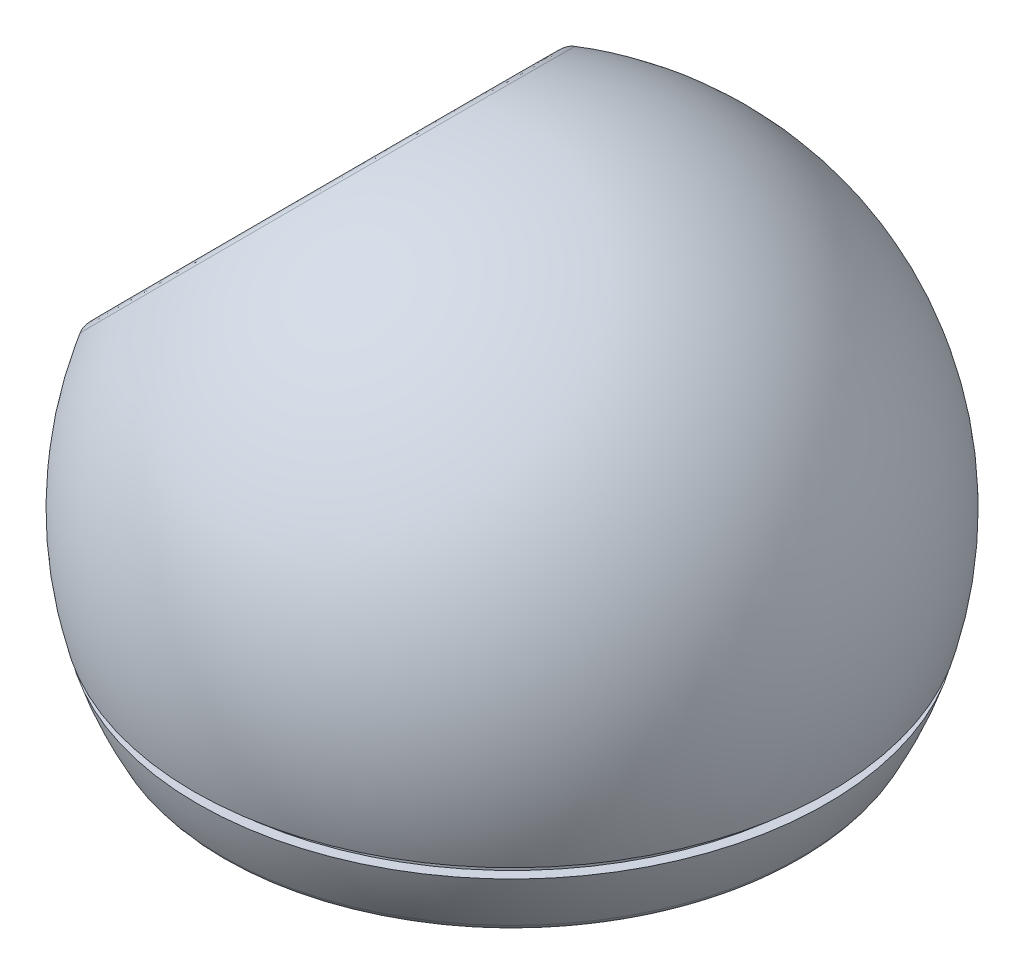
SolidWorks part; units mm, degrees
ref_plane "Front Plane" through (0, 0, 0) normal (0, 0, 1) x (1, 0, 0)
ref_plane "Top Plane" through (0, 0, 0) normal (0, 1, 0) x (1, 0, 0)
ref_plane "Right Plane" through (0, 0, 0) normal (1, 0, 0) x (0, 0, -1)
sketch "Sketch2" plane through (0, 0, 0) normal (1, 0, 0) x (0, 0, -1)
  line L0 (0, 0) -> (0, 55.0684) construction
  line L1 (0, 40) -> (0, -40)
  arc A0 (0, 40) -> (0, -40) centre (0, 0) ccw
  dimension "D1" = 80
revolve "Revolve4" add sketch "Sketch2" angle 360 about L0
sketch "Sketch3" plane through (0, 0, 0) normal (0, 0, 1) x (1, 0, 0)
  line L0 (0, 0) -> (0, -20) construction
  line L2 (-40, -20) -> (40, -20)
  line L3 (-40, -20) -> (-40, -70)
  line L4 (-40, -70) -> (40, -70)
  line L5 (40, -20) -> (40, -70)
  point P7 (0, -20)
  dimension "D1" = 20
  dimension "D2" = 80
  dimension "D3" = 50
extrude "Cut-Extrude1" cut sketch "Sketch3" against normal through all and the other way through all
sketch "Sketch4" plane through (0, 0, 0) normal (0, 0, 1) x (1, 0, 0)
  line L0 (-22.3051, 0) -> (0, 0) construction
  line L1 (0, 0) -> (-22.6274, 22.6274) construction
  line L2 (-40.2644, 4.9092) -> (-4.9904, 40.3457)
  line L3 (-4.9904, 40.3457) -> (-21.3315, 54.0701)
  line L4 (-21.3315, 54.0701) -> (-80.217, 4.9092)
  line L5 (-80.217, 4.9092) -> (-40.2644, 4.9092)
  point P6 (-22.6274, 22.6274)
  dimension "D1" = 45
  dimension "D2" = 50
  dimension "D3" = 32
extrude "Cut-Extrude2" cut sketch "Sketch4" against normal through all and the other way through all
sketch "Sketch5" plane through (-22.6793, 22.5753, 0) normal (-0.7087, 0.7055, 0) x (0, 0, 1)
  line L0 (-15.8, 18.6) -> (15.8, 18.6) construction
  line L1 (-15.8, 18.6) -> (-15.8, -21) construction
  line L2 (-15.8, -21) -> (15.8, -21) construction
  line L3 (15.8, 18.6) -> (15.8, -21) construction
  line L4 (-15.8, 16.2) -> (15.8, 16.2) construction
  line L5 (-14.2, 18.6) -> (-14.2, -21) construction
  line L6 (14.2, 18.6) -> (14.2, -21) construction
  line L7 (-15.8, -16.2) -> (15.8, -16.2) construction
  line L8 (-20.2, 22.2) -> (20.2, 22.2) construction
  line L9 (-9.2, 16.2) -> (9.2, 16.2)
  line L10 (-14.2, 11.2) -> (-14.2, -11.2)
  line L11 (-9.2, -16.2) -> (9.2, -16.2)
  line L12 (14.2, 11.2) -> (14.2, -11.2)
  line L13 (20.2, 22.2) -> (20.2, -22.2) construction
  line L14 (-20.2, -22.2) -> (20.2, -22.2) construction
  line L15 (-20.2, 22.2) -> (-20.2, -22.2) construction
  line L16 (0, 16.2) -> (0, -16.2) construction
  line L17 (15.2, 11.2) -> (15.2, -11.2)
  line L18 (-9.2, -17.2) -> (9.2, -17.2)
  line L19 (-15.2, 11.2) -> (-15.2, -11.2)
  line L20 (-9.2, 17.2) -> (9.2, 17.2)
  arc A0 (9.2, -16.2) -> (14.2, -11.2) centre (9.2, -11.2) ccw
  arc A1 (-14.2, -11.2) -> (-9.2, -16.2) centre (-9.2, -11.2) ccw
  arc A2 (9.2, 16.2) -> (14.2, 11.2) centre (9.2, 11.2) cw
  arc A3 (-9.2, 16.2) -> (-14.2, 11.2) centre (-9.2, 11.2) ccw
  arc A4 (9.2, 17.2) -> (15.2, 11.2) centre (9.2, 11.2) cw
  arc A5 (9.2, -17.2) -> (15.2, -11.2) centre (9.2, -11.2) ccw
  arc A6 (-15.2, -11.2) -> (-9.2, -17.2) centre (-9.2, -11.2) ccw
  arc A7 (-9.2, 17.2) -> (-15.2, 11.2) centre (-9.2, 11.2) ccw
  point P24 (14.2, -16.2)
  point P31 (-14.2, 16.2)
  dimension "D1" = 5
  dimension "D2" = 1
extrude "Cut-Extrude3" cut sketch "Sketch5" against normal blind 1
sketch "Sketch6" plane through (-22.6793, 22.5753, 0) normal (-0.7087, 0.7055, 0) x (0, 0, 1)
  line L0 (0, 0) -> (0, -20) construction
  circle A0 centre (0, -20) radius 1
  circle A1 centre (3, -20) radius 1
  circle A2 centre (6, -20) radius 1
  circle A3 centre (-3, -20) radius 1
  circle A4 centre (-6, -20) radius 1
  dimension "D2" = 3
  dimension "D1" = 20
  dimension "D3" = 3
extrude "Cut-Extrude4" cut sketch "Sketch6" against normal blind 1
fillet "Fillet1" radius 2 1 edges at (-5.7477, 39.5849, 0)
sketch "Sketch7" plane through (0, 0, 0) normal (1, 0, 0) x (0, 0, -1)
  line L0 (-34.641, -20) -> (34.641, -20) construction
  line L1 (-39.8854, -10.5) -> (-36.8854, -10.5)
  line L2 (-39.8854, -10.5) -> (-39.8854, -12)
  line L3 (-39.8854, -12) -> (-36.8854, -12)
  line L4 (-36.8854, -10.5) -> (-36.8854, -12)
  line L5 (-39.8854, -10.5) -> (-36.8854, -12) construction
  line L6 (-39.8854, -12) -> (-36.8854, -10.5) construction
  line L7 (0, 0) -> (0, 10.4402) construction
  arc A2 (34.641, -20) -> (-34.641, -20) centre (0, 0) ccw construction
  point P0 (-38.3854, -11.25)
  dimension "D1" = 3
  dimension "D2" = 1.5
  dimension "D3" = 8.75
revolve "Cut-Revolve1" cut sketch "Sketch7" angle 360 about L7
fillet "Fillet2" radius 2 1 edges at (-34.641, -20, 0)
